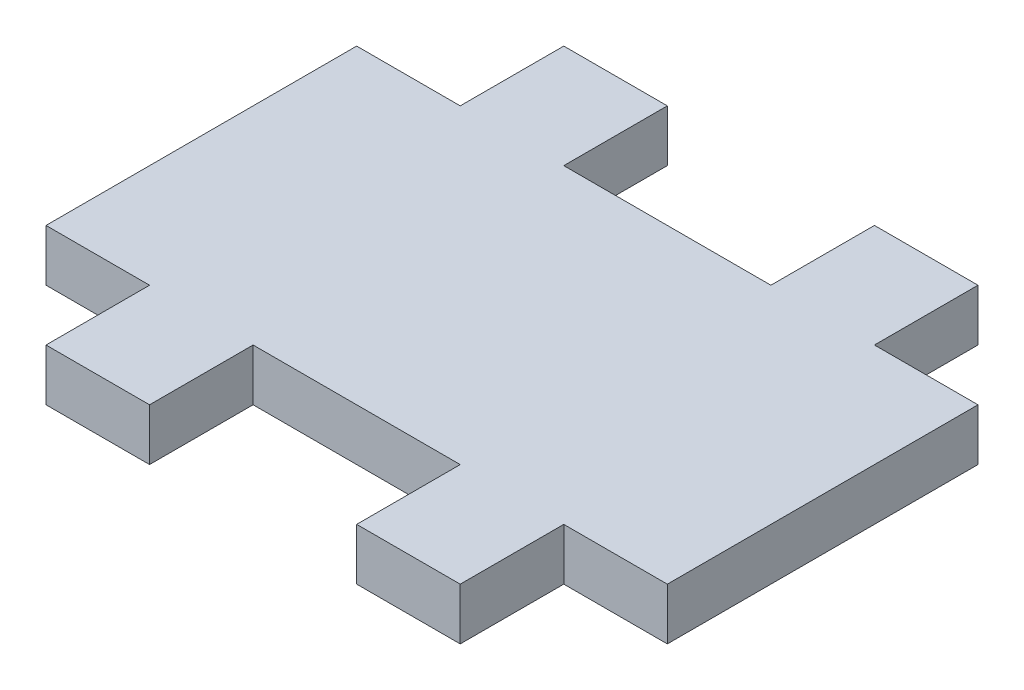
SolidWorks part; units mm, degrees
ref_plane "Front Plane" through (0, 0, 0) normal (0, 0, 1) x (1, 0, 0)
ref_plane "Top Plane" through (0, 0, 0) normal (0, 1, 0) x (1, 0, 0)
ref_plane "Right Plane" through (0, 0, 0) normal (1, 0, 0) x (0, 0, -1)
sketch "Sketch1" plane through (0, 0, 0) normal (0, 0, 1) x (1, 0, 0)
  line L1 (-98.6231, 254.1876) -> (-60.5231, 254.1876)
  line L2 (-98.6231, 254.1876) -> (-98.6231, 251.0126)
  line L3 (-98.6231, 251.0126) -> (-60.5231, 251.0126)
  line L4 (-60.5231, 254.1876) -> (-60.5231, 251.0126)
  dimension "D1" = 38.1
  dimension "D2" = 3.175
extrude "Boss-Extrude1" add sketch "Sketch1" against normal up to surface (31.75 mm away) contours L1 L4 L3 L2
sketch "Sketch2" plane through (0, 254.1876, 0) normal (0, 1, 0) x (1, 0, 0)
  line L0 (-140.0225, 25.4) -> (-17.1273, 25.4) construction
  line L1 (-98.6231, 31.75) -> (-92.2731, 31.75)
  line L2 (-98.6231, 31.75) -> (-98.6231, 25.4)
  line L3 (-98.6231, 25.4) -> (-92.2731, 25.4)
  line L4 (-92.2731, 31.75) -> (-92.2731, 25.4)
  line L5 (-98.6231, 31.75) -> (-60.5231, 31.75) construction
  line L6 (-85.9231, 31.75) -> (-73.2231, 31.75)
  line L7 (-85.9231, 31.75) -> (-85.9231, 25.4)
  line L8 (-85.9231, 25.4) -> (-73.2231, 25.4)
  line L9 (-73.2231, 31.75) -> (-73.2231, 25.4)
  line L10 (-17.1273, 6.35) -> (-140.0225, 6.35) construction
  line L11 (-60.5231, 31.75) -> (-66.8731, 31.75)
  line L12 (-60.5231, 31.75) -> (-60.5231, 25.4)
  line L13 (-60.5231, 25.4) -> (-66.8731, 25.4)
  line L14 (-66.8731, 31.75) -> (-66.8731, 25.4)
  line L15 (-98.6231, 0) -> (-92.2731, 0)
  line L16 (-98.6231, 0) -> (-98.6231, 6.35)
  line L17 (-98.6231, 6.35) -> (-92.2731, 6.35)
  line L18 (-92.2731, 0) -> (-92.2731, 6.35)
  line L19 (-98.6231, 0) -> (-60.5231, 0) construction
  line L20 (-85.9231, 0) -> (-73.2231, 0)
  line L21 (-85.9231, 0) -> (-85.9231, 6.35)
  line L22 (-85.9231, 6.35) -> (-73.2231, 6.35)
  line L23 (-73.2231, 0) -> (-73.2231, 6.35)
  line L25 (-60.5231, 0) -> (-66.8731, 0)
  line L26 (-60.5231, 0) -> (-60.5231, 6.35)
  line L27 (-60.5231, 6.35) -> (-66.8731, 6.35)
  line L28 (-66.8731, 0) -> (-66.8731, 6.35)
  dimension "D1" = 6.35
  dimension "D2" = 6.35
  dimension "D3" = 6.35
  dimension "D4" = 6.35
  dimension "D5" = 6.35
  dimension "D6" = 6.35
  dimension "D7" = 6.35
  dimension "D8" = 6.35
extrude "Cut-Extrude1" cut sketch "Sketch2" against normal through all
